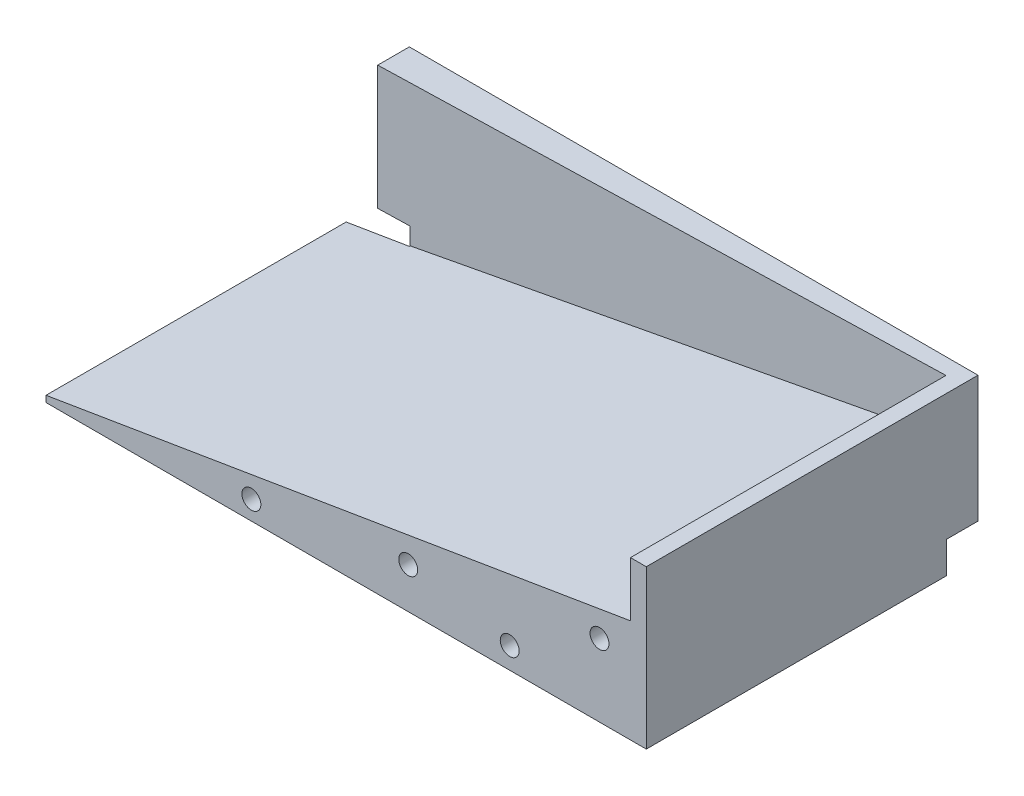
SolidWorks part; units mm, degrees
ref_plane "Plan de face" through (0, 0, 0) normal (0, 0, 1) x (1, 0, 0)
ref_plane "Plan de dessus" through (0, 0, 0) normal (0, 1, 0) x (1, 0, 0)
ref_plane "Plan de droite" through (0, 0, 0) normal (1, 0, 0) x (0, 0, -1)
sketch "Esquisse1" plane through (0, 0, 0) normal (0, 0, 1) x (1, 0, 0)
  line L0 (-105.796, 0) -> (84.204, 0)
  line L1 (84.204, 0) -> (84.204, 33.5021)
  line L2 (84.204, 25.3929) -> (-68.9493, 0) construction
  line L3 (-105.796, 0) -> (-105.796, 2)
  line L4 (-105.796, 2) -> (84.204, 33.5021)
  line L5 (40.9815, 6.7762) -> (8.8615, 12.9011) construction
  line L6 (69.406, 22.9394) -> (40.9815, 6.7762) construction
  circle A0 centre (69.406, 22.9394) radius 3
  circle A1 centre (40.9815, 6.7762) radius 3
  circle A2 centre (-40.796, 6) radius 3
  circle A3 centre (8.8615, 12.9011) radius 3
  dimension "D3" = 6
  dimension "D6" = 6
  dimension "D8" = 6
  dimension "D11" = 6
  dimension "D1" = 190
  dimension "D2" = 2
  dimension "D4" = 15
  dimension "D7" = 8
  dimension "D9" = 6
  dimension "D10" = 65
extrude "Boss.-Extru.1" add sketch "Esquisse1" along normal blind 200
sketch "Esquisse4" plane through (84.204, 0, 0) normal (1, 0, 0) x (0, 0, -1)
  line L1 (-200, 0) -> (-205, 0)
  line L2 (-200, 0) -> (-200, 50)
  line L3 (-200, 50) -> (-205, 50)
  line L4 (-205, 0) -> (-205, 50)
  line L5 (0, 0) -> (5, 0)
  line L6 (0, 0) -> (0, 50)
  line L7 (0, 50) -> (5, 50)
  line L8 (5, 0) -> (5, 50)
  dimension "D1" = 50
  dimension "D2" = 5
  dimension "D3" = 5
  dimension "D4" = 50
extrude "Boss.-Extru.4" add sketch "Esquisse4" against normal blind 180
sketch "Esquisse8" plane through (0, 50, 0) normal (0, 1, 0) x (1, 0, 0)
  line L0 (84.204, 0) -> (-95.796, 0)
  line L1 (-95.796, 0) -> (-95.796, -5)
  line L2 (-95.796, -5) -> (84.204, 0)
  dimension "D1" = 5
extrude "Boss.-Extru.7" add sketch "Esquisse8" against normal up to surface (50 mm away)
ref_plane "Plan2" through (-5.796, 0, 0) normal (1, 0, 0) x (0, 0, -1)
sketch "Esquisse6" plane through (0, 0, -5) normal (0, 0, -1) x (-1, 0, 0)
  line L1 (105.796, 0) -> (85.796, 0)
  line L2 (105.796, 0) -> (105.796, 10.7198)
  line L3 (105.796, 10.7198) -> (85.796, 10.7198)
  line L4 (85.796, 0) -> (85.796, 10.7198)
  line L5 (95.796, 0) -> (95.796, 50) construction
  dimension "D1" = 10
extrude "Enlèv. mat.-Extru.2" cut sketch "Esquisse6" against normal blind 10
ref_plane "Plan3" through (0, 0, 100) normal (0, 0, -1) x (-1, 0, 0)
sketch "Esquisse5" plane through (84.204, 0, 0) normal (1, 0, 0) x (0, 0, -1)
  line L1 (-205, 0) -> (-195, 0)
  line L2 (-205, 0) -> (-205, 10)
  line L3 (-205, 10) -> (-195, 10)
  line L4 (-195, 0) -> (-195, 10)
  line L5 (5, 0) -> (-5, 0)
  line L6 (5, 0) -> (5, 10)
  line L7 (5, 10) -> (-5, 10)
  line L8 (-5, 0) -> (-5, 10)
  dimension "D1" = 10
  dimension "D2" = 10
  dimension "D3" = 10
  dimension "D4" = 10
extrude "Enlèv. mat.-Extru.1" cut sketch "Esquisse5" against normal blind 10
sketch "Esquisse14" plane through (0, 0, -5) normal (0, 0, -1) x (-1, 0, 0)
  circle A0 centre (-69.406, 22.9394) radius 5
  circle A1 centre (-40.9815, 6.7762) radius 5
  circle A2 centre (-8.8615, 12.9011) radius 5
  circle A3 centre (40.796, 6) radius 5
  dimension "D1" = 10
  dimension "D2" = 10
  dimension "D3" = 10
  dimension "D4" = 10
extrude "Enlèv. mat.-Extru.4" cut sketch "Esquisse14" against normal blind 15
mirror "Symétrie3" about plane through (0, 0, 100) normal (0, 0, -1) of "Enlèv. mat.-Extru.4", "Boss.-Extru.7", "Enlèv. mat.-Extru.2"
sketch "Esquisse15" plane through (0, 0, -5) normal (0, 0, -1) x (-1, 0, 0)
  line L0 (-84.204, 33.5021) -> (-79.204, 32.6731)
  line L1 (-84.204, 33.5021) -> (85.796, 5.316) construction
  line L2 (-79.204, 32.6731) -> (-79.204, 50)
  line L3 (95.796, 50) -> (-84.204, 50) construction
  line L4 (-79.204, 50) -> (-84.204, 50)
  line L5 (-84.204, 50) -> (-84.204, 33.5021)
  dimension "D1" = 5
extrude "Boss.-Extru.8" add sketch "Esquisse15" against normal up to surface (204.8611 mm away)
sketch "Esquisse16" plane through (0, 0, 100) normal (0, 0, -1) x (-1, 0, 0)
  line L0 (5.796, 27.5) -> (5.796, -27.5) construction
  line L1 (115.3505, 63.1576) -> (-103.7585, 63.1576)
  line L2 (115.3505, 63.1576) -> (115.3505, -5.3252)
  line L3 (115.3505, -5.3252) -> (-103.7585, -5.3252)
  line L4 (-103.7585, 63.1576) -> (-103.7585, -5.3252)
  line L5 (115.3505, 63.1576) -> (-103.7585, -5.3252) construction
  line L6 (115.3505, -5.3252) -> (-103.7585, 63.1576) construction
  point P0 (5.796, 28.9162)
extrude "Enlèv. mat.-Extru.5" cut sketch "Esquisse16" against normal up to surface (105 mm away) up to face at (-45.796, 6, 205)
